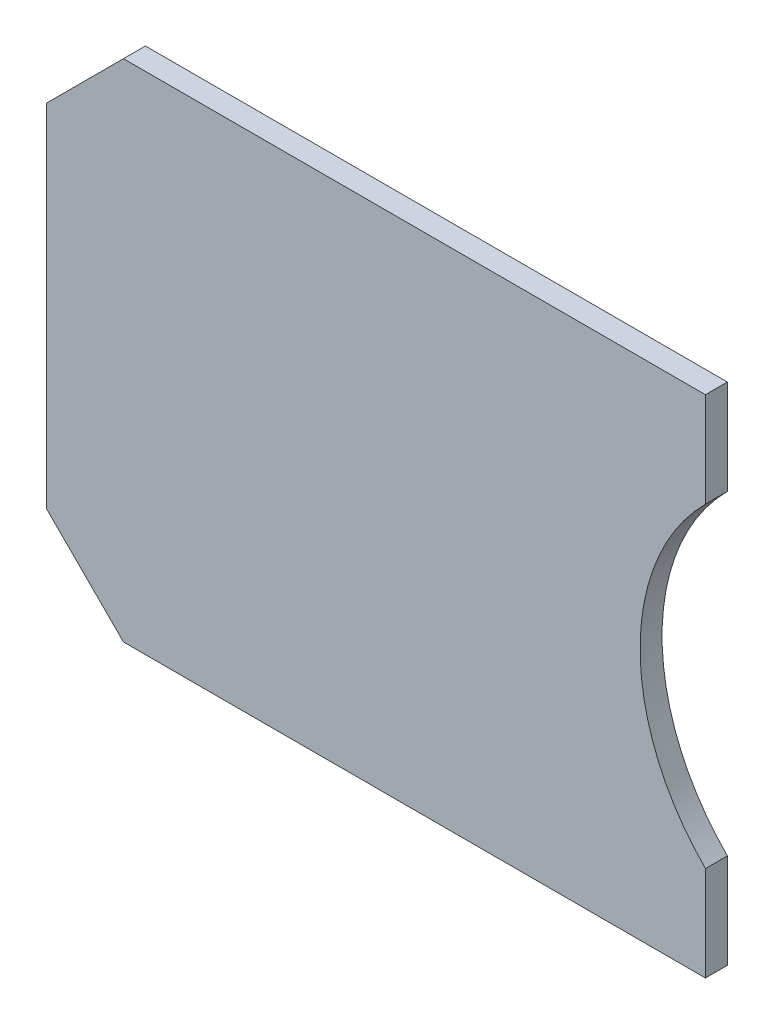
SolidWorks part; units mm, degrees
ref_plane "Front Plane" through (0, 0, 0) normal (0, 0, 1) x (1, 0, 0)
ref_plane "Top Plane" through (0, 0, 0) normal (0, 1, 0) x (1, 0, 0)
ref_plane "Right Plane" through (0, 0, 0) normal (1, 0, 0) x (0, 0, -1)
sketch "Эскиз1" plane through (0, 0, 0) normal (0, 0, 1) x (1, 0, 0)
  line L0 (20.1524, -9.568) -> (17.45, -9.568) construction
  line L1 (20.45, -8.8495) -> (20.45, -8.418)
  line L2 (17.8, -8.418) -> (17.45, -8.768)
  line L3 (17.45, -8.768) -> (17.45, -10.368)
  line L4 (20.45, -8.418) -> (17.8, -8.418)
  line L5 (20.45, -10.2865) -> (20.45, -10.718)
  line L6 (17.8, -10.718) -> (17.45, -10.368)
  line L7 (20.45, -10.718) -> (17.8, -10.718)
  arc A0 (20.45, -8.8495) -> (20.45, -10.2865) centre (21.1685, -9.568) ccw construction
  arc A1 (20.45, -8.8495) -> (20.45, -10.2865) centre (21.1685, -9.568) ccw
  dimension "D1" = 2.3
  dimension "D2" = 45
  dimension "D3" = 1.6
  dimension "D4" = 3
extrude "Бобышка-Вытянуть1" add sketch "Эскиз1" along normal blind 0.1 contours L7 L6 L3 L2 L4 L1 A1 L5
